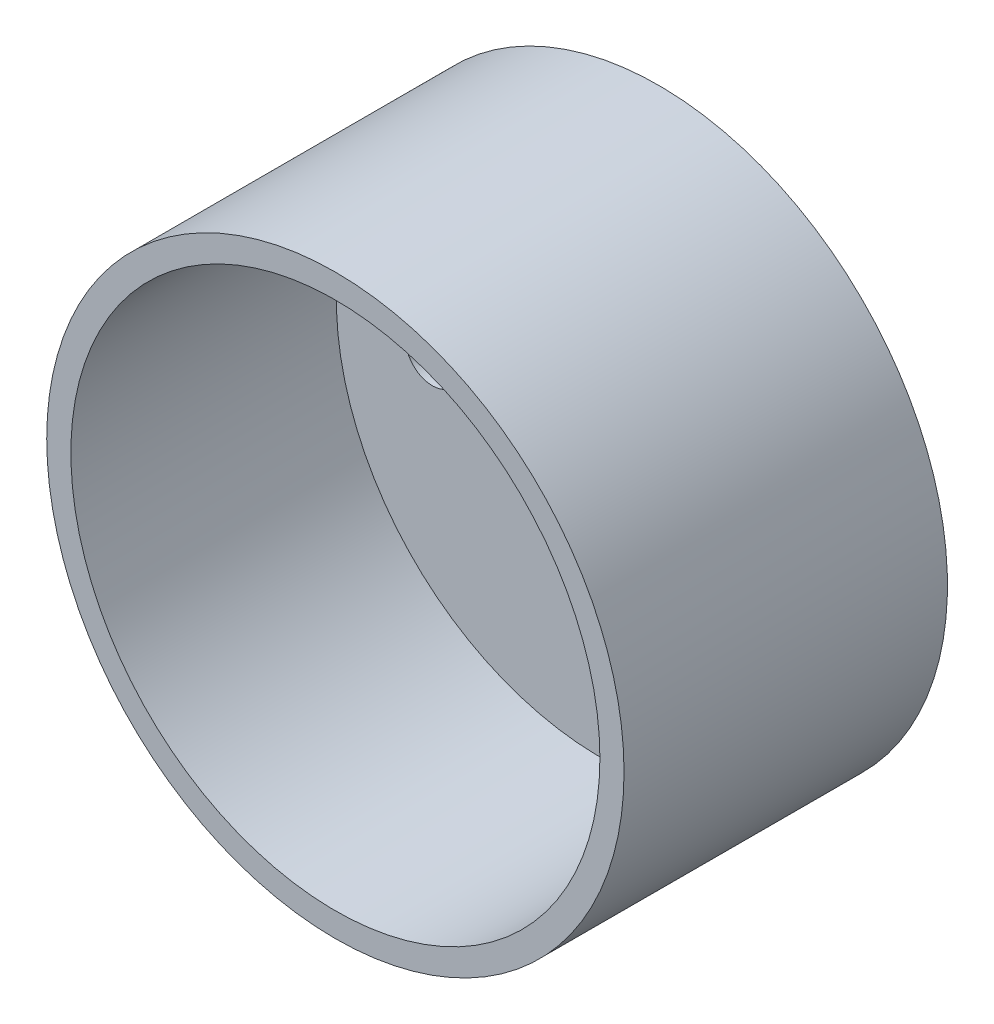
SolidWorks part; units mm, degrees
ref_plane "Front Plane" through (0, 0, 0) normal (0, 0, 1) x (1, 0, 0)
ref_plane "Top Plane" through (0, 0, 0) normal (0, 1, 0) x (1, 0, 0)
ref_plane "Right Plane" through (0, 0, 0) normal (1, 0, 0) x (0, 0, -1)
sketch "Sketch1" plane through (0, 0, 0) normal (0, 0, 1) x (1, 0, 0)
  circle A0 centre (0, 0) radius 54.8
  circle A1 centre (0, 0) radius 59.8
  dimension "D1" = 109.6
  dimension "D2" = 5
extrude "Boss-Extrude1" add sketch "Sketch1" along normal blind 55
sketch "Sketch2" plane through (0, 0, 0) normal (0, 0, -1) x (-1, 0, 0)
  line L0 (15, 0) -> (54.8, 0) construction
  circle A0 centre (0, 0) radius 59.8 construction
  circle A1 centre (0, 0) radius 59.8
  circle A2 centre (0, 0) radius 15
  circle A3 centre (34.9, 0) radius 5.5562
  circle A4 centre (0, 0) radius 54.8 construction
  point P11 (42.4, 0)
  dimension "D1" = 30
  dimension "D2" = 11.1125
extrude "Boss-Extrude2" add sketch "Sketch2" along normal blind 12
